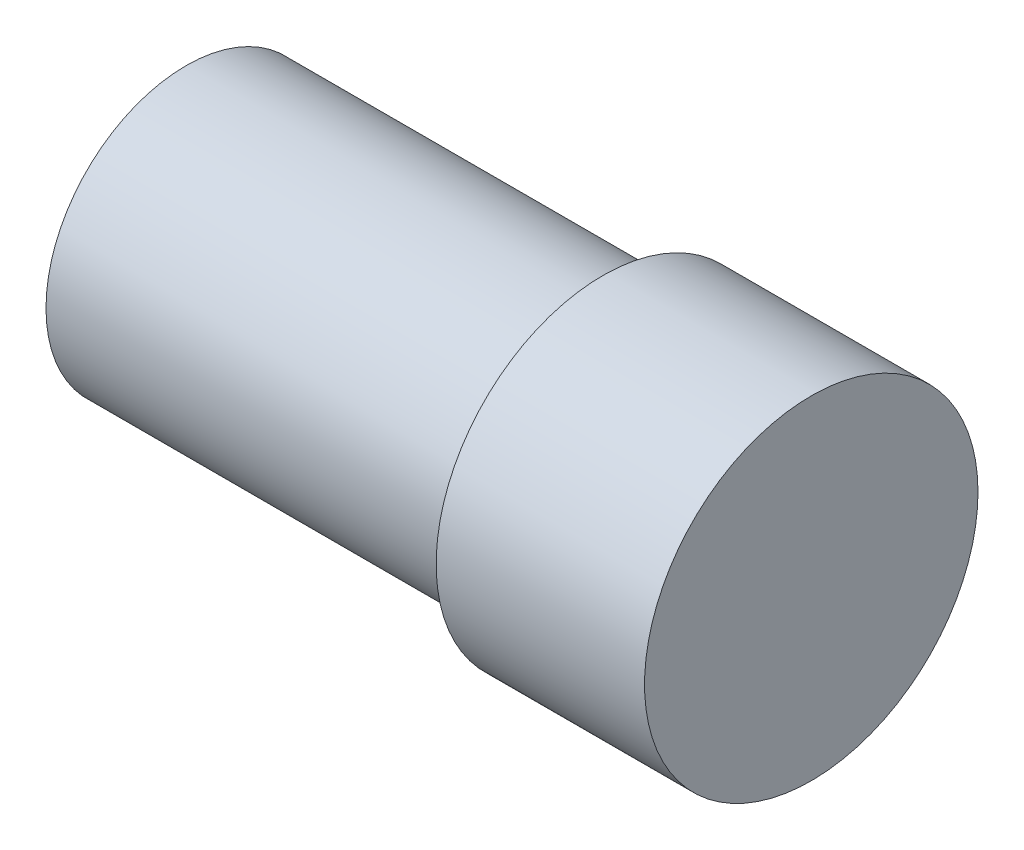
SolidWorks part; units mm, degrees
material "ABS"
ref_plane "Front Plane" through (0, 0, 0) normal (0, 0, 1) x (1, 0, 0)
ref_plane "Top Plane" through (0, 0, 0) normal (0, 1, 0) x (1, 0, 0)
ref_plane "Right Plane" through (0, 0, 0) normal (1, 0, 0) x (0, 0, -1)
sketch "Sketch1" plane through (0, 0, 0) normal (1, 0, 0) x (0, 0, -1)
  circle A0 centre (0, 0) radius 5.08
  dimension "D1" = 10.16
extrude "Boss-Extrude1" add sketch "Sketch1" along normal blind 6.35
sketch "Sketch2" plane through (0, 0, 0) normal (-1, 0, 0) x (0, 0, 1)
  circle A0 centre (0, 0) radius 4.2672
  dimension "D1" = 8.5344
extrude "Boss-Extrude2" add sketch "Sketch2" along normal blind 12.7
hole_wizard "#21 (0.159) Diameter Hole1" positions "Sketch4" profile "Sketch3" hole size "#21" standard "ANSI Inch"
sketch "Sketch4" plane through (-12.7, 0, 0) normal (-1, 0, 0) x (0, 0, 1)
  point P0 (0, 0)
sketch "Sketch3" plane through (-12.7, 0, 0) normal (0, 1, 0) x (0, 0, 1)
  line L0 (0, 0) -> (0, 12.7)
  line L1 (0, 12.7) -> (2, 12.7)
  line L2 (2, 12.7) -> (2, 0)
  line L5 (2, 0) -> (0, 0)
  line L10 (0, 12.7) -> (-2, 12.7) construction
  line L11 (0, -6.35) -> (0, 107.95) construction
  dimension "Hole Dia." = 4
  dimension "Hole Depth" = 12.7
  dimension "Drill Angle" = 180
